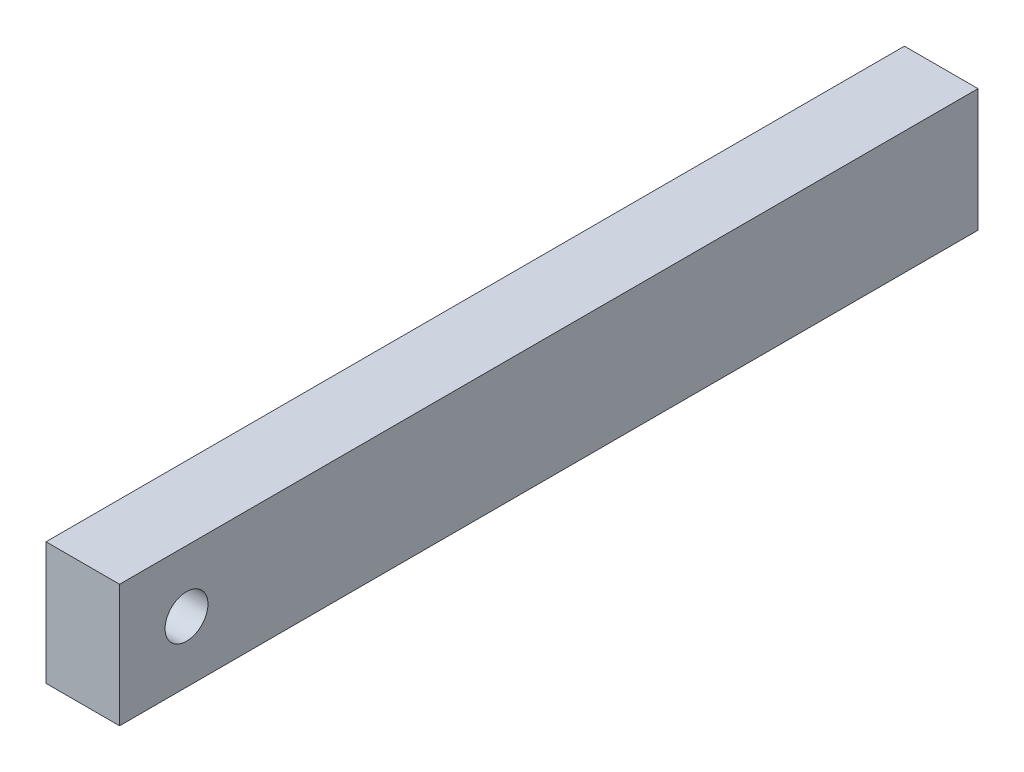
SolidWorks part; units mm, degrees
ref_plane "Plano frontal" through (0, 0, 0) normal (0, 0, 1) x (1, 0, 0)
ref_plane "Plano superior" through (0, 0, 0) normal (0, 1, 0) x (1, 0, 0)
ref_plane "Plano direito" through (0, 0, 0) normal (1, 0, 0) x (0, 0, -1)
sketch "Esboço1" plane through (0, 0, 0) normal (0, 0, 1) x (1, 0, 0)
  line L1 (3, -5) -> (-3, -5)
  line L2 (3, -5) -> (3, 5)
  line L3 (3, 5) -> (-3, 5)
  line L4 (-3, -5) -> (-3, 5)
  line L5 (3, -5) -> (-3, 5) construction
  line L6 (3, 5) -> (-3, -5) construction
  point P0 (0, 0)
  dimension "D1" = 10
  dimension "D2" = 6
extrude "Ressalto-extrusão1" add sketch "Esboço1" along normal blind 70
sketch "Esboço2" plane through (3, 0, 0) normal (1, 0, 0) x (0, 0, -1)
  circle A0 centre (-64.5424, 0) radius 1.75
  dimension "D1" = 3.5
extrude "Corte-extrusão1" cut sketch "Esboço2" against normal through all
